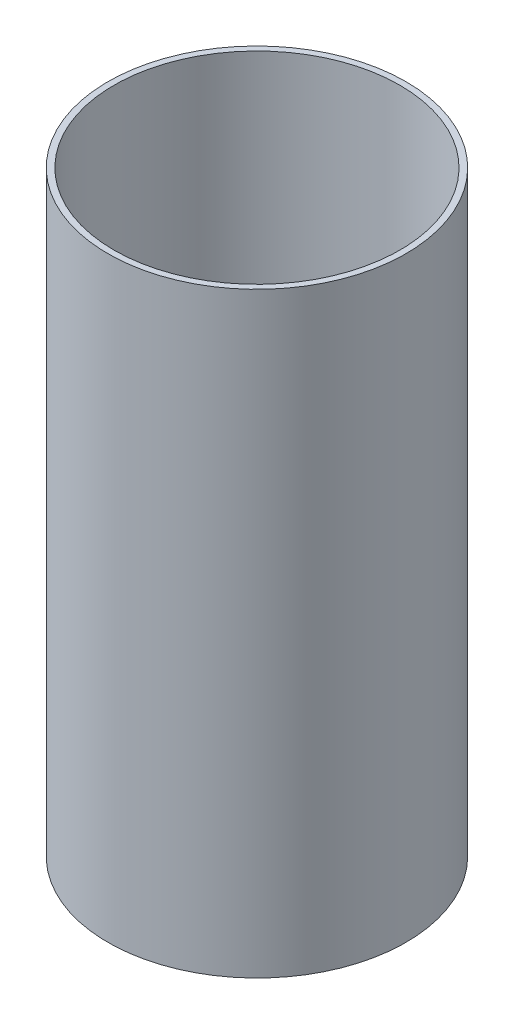
SolidWorks part; units mm, degrees
ref_plane "Front Plane" through (0, 0, 0) normal (0, 0, 1) x (1, 0, 0)
ref_plane "Top Plane" through (0, 0, 0) normal (0, 1, 0) x (1, 0, 0)
ref_plane "Right Plane" through (0, 0, 0) normal (1, 0, 0) x (0, 0, -1)
sketch "Sketch1" plane through (0, 0, 0) normal (0, 1, 0) x (1, 0, 0)
  circle A0 centre (0, 0) radius 38.0746
  circle A1 centre (0, 0) radius 36.5125
  dimension "D1" = 76.1492
  dimension "D2" = 73.025
extrude "Boss-Extrude1" add sketch "Sketch1" along normal blind 152.4
